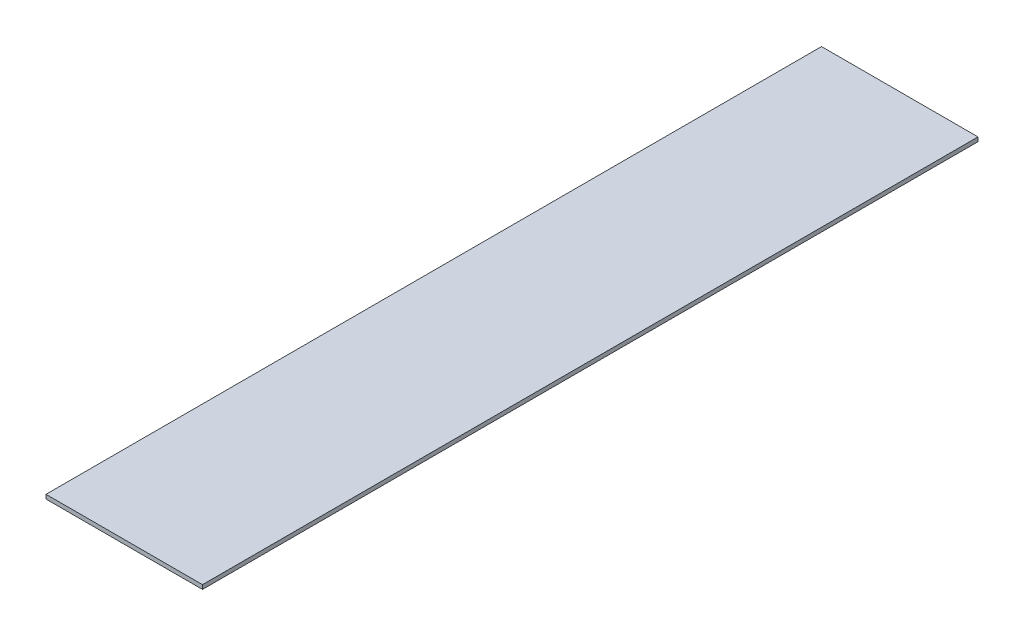
SolidWorks part; units mm, degrees
ref_plane "Front Plane" through (0, 0, 0) normal (0, 0, 1) x (1, 0, 0)
ref_plane "Top Plane" through (0, 0, 0) normal (0, 1, 0) x (1, 0, 0)
ref_plane "Right Plane" through (0, 0, 0) normal (1, 0, 0) x (0, 0, -1)
sketch "Sketch1" plane through (0, 0, 0) normal (0, 1, 0) x (1, 0, 0)
  line L1 (0, 0) -> (113, 0)
  line L2 (0, 0) -> (0, 560)
  line L3 (0, 560) -> (113, 560)
  line L4 (113, 0) -> (113, 560)
  dimension "D1" = 560
  dimension "D2" = 113
extrude "Boss-Extrude1" add sketch "Sketch1" along normal blind 3
